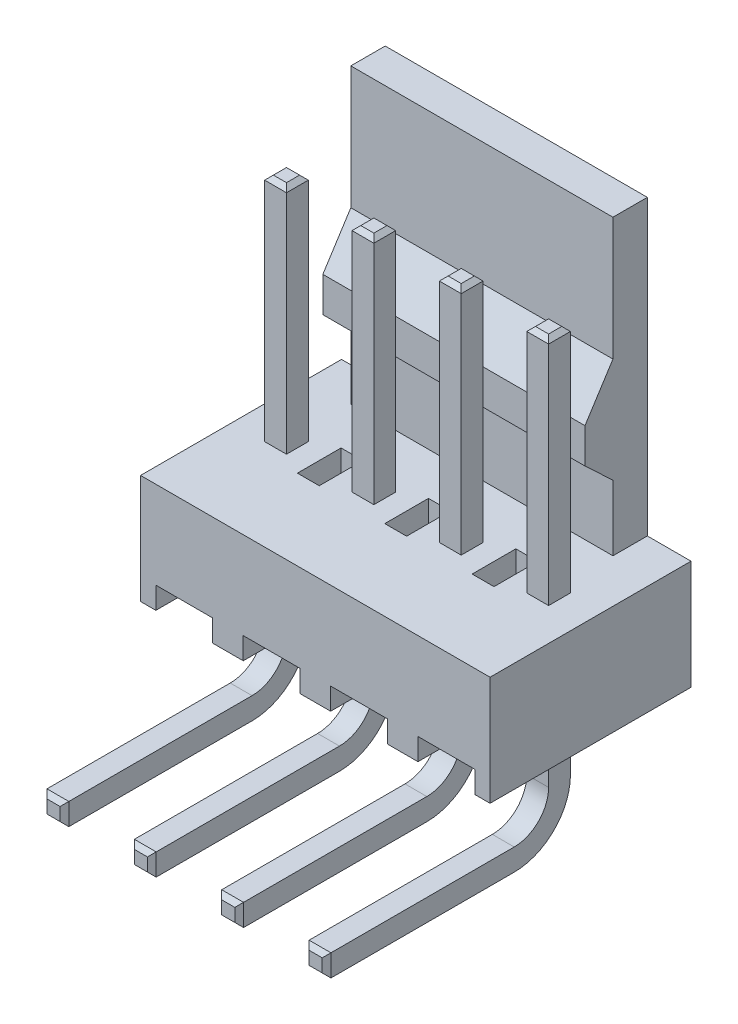
SolidWorks part; units mm, degrees
ref_plane "Front" through (0, 0, 0) normal (0, 0, 1) x (1, 0, 0)
ref_plane "Top" through (0, 0, 0) normal (0, 1, 0) x (1, 0, 0)
ref_plane "Right" through (0, 0, 0) normal (1, 0, 0) x (0, 0, -1)
ref_plane "Plane1" through (0, -1.5875, 0) normal (0, -1, 0) x (1, 0, 0)
sketch "Sketch1" plane through (0, -1.5875, 0) normal (0, -1, 0) x (1, 0, 0)
  line L0 (-5.08, -2.8702) -> (3.81, -2.8702)
  line L1 (3.81, -2.8702) -> (3.81, 2.9718)
  line L2 (3.81, 2.9718) -> (-5.08, 2.9718)
  line L3 (-5.08, 2.9718) -> (-5.08, -2.8702)
extrude "Boss-Extrude1" add sketch "Sketch1" against normal blind 3.175
ref_plane "Plane2" through (3.81, 0, 0) normal (1, 0, 0) x (0, 0, -1)
sketch "Sketch2" plane through (3.81, 0, 0) normal (1, 0, 0) x (0, 0, -1)
  line L0 (0.651, 4.6355) -> (1.8702, 3.4925)
  line L1 (1.8702, 3.4925) -> (1.8702, 1.5875)
  line L2 (1.8702, 1.5875) -> (2.8702, 1.5875)
  line L3 (2.8702, 1.5875) -> (2.8702, 10.1125)
  line L4 (2.8702, 10.1125) -> (1.8702, 10.1125)
  line L5 (1.8702, 10.1125) -> (1.8702, 6.5405)
  line L6 (1.8702, 6.5405) -> (0.651, 4.6355)
extrude "Boss-Extrude2" add sketch "Sketch2" against normal blind 7.62
sketch "Sketch3" plane through (3.81, 0, 0) normal (1, 0, 0) x (0, 0, -1)
  line L0 (-2.9718, 1.5875) -> (2.8702, 1.5875)
  line L1 (2.8702, 1.5875) -> (2.8702, -1.5875)
  line L2 (2.8702, -1.5875) -> (-2.9718, -1.5875)
  line L3 (-2.9718, -1.5875) -> (-2.9718, 1.5875)
extrude "Boss-Extrude3" add sketch "Sketch3" along normal blind 1.27
sketch "Sketch4" plane through (0, 0, -2.8702) normal (0, 0, -1) x (-1, 0, 0)
  line L0 (0.4445, -1.5875) -> (2.0955, -1.5875)
  line L1 (2.0955, -1.5875) -> (2.0955, -0.9525)
  line L2 (2.0955, -0.9525) -> (0.4445, -0.9525)
  line L3 (0.4445, -0.9525) -> (0.4445, -1.5875)
extrude "Cut-Extrude1" cut sketch "Sketch4" against normal through all
sketch "Sketch5" plane through (0, -0.9525, 0) normal (0, -1, 0) x (1, 0, 0)
  line L0 (-0.9525, -0.3175) -> (-1.5875, -0.3175)
  line L1 (-1.5875, -0.3175) -> (-1.5875, 0.3175)
  line L2 (-1.5875, 0.3175) -> (-0.9525, 0.3175)
  line L3 (-0.9525, 0.3175) -> (-0.9525, -0.3175)
extrude "Boss-Extrude4" add sketch "Sketch5" along normal blind 3.6725
sketch "Sketch6" plane through (0, 0, 0.3175) normal (0, 0, 1) x (1, 0, 0)
  line L0 (-0.9525, -3.99) -> (-0.9525, -4.625)
  line L1 (-0.9525, -4.625) -> (-1.5875, -4.625)
  line L2 (-1.5875, -4.625) -> (-1.5875, -3.99)
  line L3 (-1.5875, -3.99) -> (-0.9525, -3.99)
extrude "Boss-Extrude5" add sketch "Sketch6" along normal blind 6.4543
sketch "Sketch7" plane through (0, 0, -2.8702) normal (0, 0, -1) x (-1, 0, 0)
  line L0 (-2.0955, -1.5875) -> (-0.4445, -1.5875)
  line L1 (-0.4445, -1.5875) -> (-0.4445, -0.9525)
  line L2 (-0.4445, -0.9525) -> (-2.0955, -0.9525)
  line L3 (-2.0955, -0.9525) -> (-2.0955, -1.5875)
extrude "Cut-Extrude2" cut sketch "Sketch7" against normal through all
sketch "Sketch8" plane through (0, -0.9525, 0) normal (0, -1, 0) x (1, 0, 0)
  line L0 (1.5875, -0.3175) -> (0.9525, -0.3175)
  line L1 (0.9525, -0.3175) -> (0.9525, 0.3175)
  line L2 (0.9525, 0.3175) -> (1.5875, 0.3175)
  line L3 (1.5875, 0.3175) -> (1.5875, -0.3175)
extrude "Boss-Extrude6" add sketch "Sketch8" along normal blind 3.6725
sketch "Sketch9" plane through (0, 0, 0.3175) normal (0, 0, 1) x (1, 0, 0)
  line L0 (1.5875, -4.625) -> (0.9525, -4.625)
  line L1 (0.9525, -4.625) -> (0.9525, -3.99)
  line L2 (0.9525, -3.99) -> (1.5875, -3.99)
  line L3 (1.5875, -3.99) -> (1.5875, -4.625)
extrude "Boss-Extrude7" add sketch "Sketch9" along normal blind 6.4543
sketch "Sketch10" plane through (0, 0, -2.8702) normal (0, 0, -1) x (-1, 0, 0)
  line L0 (2.9845, -1.5875) -> (4.6355, -1.5875)
  line L1 (4.6355, -1.5875) -> (4.6355, -0.9525)
  line L2 (4.6355, -0.9525) -> (2.9845, -0.9525)
  line L3 (2.9845, -0.9525) -> (2.9845, -1.5875)
extrude "Cut-Extrude3" cut sketch "Sketch10" against normal through all
sketch "Sketch11" plane through (0, -0.9525, 0) normal (0, -1, 0) x (1, 0, 0)
  line L0 (-3.4925, -0.3175) -> (-4.1275, -0.3175)
  line L1 (-4.1275, -0.3175) -> (-4.1275, 0.3175)
  line L2 (-4.1275, 0.3175) -> (-3.4925, 0.3175)
  line L3 (-3.4925, 0.3175) -> (-3.4925, -0.3175)
extrude "Boss-Extrude8" add sketch "Sketch11" along normal blind 3.6725
sketch "Sketch12" plane through (0, 0, 0.3175) normal (0, 0, 1) x (1, 0, 0)
  line L0 (-3.4925, -4.625) -> (-4.1275, -4.625)
  line L1 (-4.1275, -4.625) -> (-4.1275, -3.99)
  line L2 (-4.1275, -3.99) -> (-3.4925, -3.99)
  line L3 (-3.4925, -3.99) -> (-3.4925, -4.625)
extrude "Boss-Extrude9" add sketch "Sketch12" along normal blind 6.4543
sketch "Sketch13" plane through (0, 0, -2.8702) normal (0, 0, -1) x (-1, 0, 0)
  line L0 (-4.6355, -1.5875) -> (-2.9845, -1.5875)
  line L1 (-2.9845, -1.5875) -> (-2.9845, -0.9525)
  line L2 (-2.9845, -0.9525) -> (-4.6355, -0.9525)
  line L3 (-4.6355, -0.9525) -> (-4.6355, -1.5875)
extrude "Cut-Extrude4" cut sketch "Sketch13" against normal through all
sketch "Sketch14" plane through (0, -0.9525, 0) normal (0, -1, 0) x (1, 0, 0)
  line L0 (4.1275, -0.3175) -> (3.4925, -0.3175)
  line L1 (3.4925, -0.3175) -> (3.4925, 0.3175)
  line L2 (3.4925, 0.3175) -> (4.1275, 0.3175)
  line L3 (4.1275, 0.3175) -> (4.1275, -0.3175)
extrude "Boss-Extrude10" add sketch "Sketch14" along normal blind 3.6725
sketch "Sketch15" plane through (0, 0, 0.3175) normal (0, 0, 1) x (1, 0, 0)
  line L0 (4.1275, -4.625) -> (3.4925, -4.625)
  line L1 (3.4925, -4.625) -> (3.4925, -3.99)
  line L2 (3.4925, -3.99) -> (4.1275, -3.99)
  line L3 (4.1275, -3.99) -> (4.1275, -4.625)
extrude "Boss-Extrude11" add sketch "Sketch15" along normal blind 6.4543
sketch "Sketch16" plane through (0, 1.5875, 0) normal (0, 1, 0) x (-1, 0, 0)
  line L0 (-4.1275, 0.3175) -> (-3.4925, 0.3175)
  line L1 (-3.4925, 0.3175) -> (-3.4925, -0.3175)
  line L2 (-3.4925, -0.3175) -> (-4.1275, -0.3175)
  line L3 (-4.1275, -0.3175) -> (-4.1275, 0.3175)
extrude "Boss-Extrude12" add sketch "Sketch16" along normal blind 6.71
sketch "Sketch17" plane through (0, 1.5875, 0) normal (0, 1, 0) x (-1, 0, 0)
  line L0 (-0.9525, -0.3175) -> (-1.5875, -0.3175)
  line L1 (-1.5875, -0.3175) -> (-1.5875, 0.3175)
  line L2 (-1.5875, 0.3175) -> (-0.9525, 0.3175)
  line L3 (-0.9525, 0.3175) -> (-0.9525, -0.3175)
extrude "Boss-Extrude13" add sketch "Sketch17" along normal blind 6.71
sketch "Sketch18" plane through (0, 1.5875, 0) normal (0, 1, 0) x (-1, 0, 0)
  line L0 (0.9525, 0.3175) -> (1.5875, 0.3175)
  line L1 (1.5875, 0.3175) -> (1.5875, -0.3175)
  line L2 (1.5875, -0.3175) -> (0.9525, -0.3175)
  line L3 (0.9525, -0.3175) -> (0.9525, 0.3175)
extrude "Boss-Extrude14" add sketch "Sketch18" along normal blind 6.71
sketch "Sketch19" plane through (0, 1.5875, 0) normal (0, 1, 0) x (-1, 0, 0)
  line L0 (3.4925, -0.3175) -> (3.4925, 0.3175)
  line L1 (3.4925, 0.3175) -> (4.1275, 0.3175)
  line L2 (4.1275, 0.3175) -> (4.1275, -0.3175)
  line L3 (4.1275, -0.3175) -> (3.4925, -0.3175)
extrude "Boss-Extrude15" add sketch "Sketch19" along normal blind 6.71
sketch "Sketch20" plane through (0, 1.5875, 0) normal (0, 1, 0) x (-1, 0, 0)
  line L0 (-2.8575, 0.635) -> (-2.8575, -0.635)
  line L1 (-2.8575, -0.635) -> (-2.2225, -0.635)
  line L2 (-2.2225, -0.635) -> (-2.2225, 0.635)
  line L3 (-2.2225, 0.635) -> (-2.8575, 0.635)
extrude "Cut-Extrude5" cut sketch "Sketch20" against normal blind 1.27
sketch "Sketch21" plane through (0, 1.5875, 0) normal (0, 1, 0) x (-1, 0, 0)
  line L0 (-0.3175, 0.635) -> (-0.3175, -0.635)
  line L1 (-0.3175, -0.635) -> (0.3175, -0.635)
  line L2 (0.3175, -0.635) -> (0.3175, 0.635)
  line L3 (0.3175, 0.635) -> (-0.3175, 0.635)
extrude "Cut-Extrude6" cut sketch "Sketch21" against normal blind 1.27
sketch "Sketch22" plane through (0, 1.5875, 0) normal (0, 1, 0) x (-1, 0, 0)
  line L0 (2.2225, 0.635) -> (2.2225, -0.635)
  line L1 (2.2225, -0.635) -> (2.8575, -0.635)
  line L2 (2.8575, -0.635) -> (2.8575, 0.635)
  line L3 (2.8575, 0.635) -> (2.2225, 0.635)
extrude "Cut-Extrude7" cut sketch "Sketch22" against normal blind 1.27
chamfer "Chamfer1" distance 0.127 angle 45 32 edges at (-3.81, -3.99, 6.7718) (-4.1275, -4.3075, 6.7718) (-3.4925, -4.3075, 6.7718) (-3.81, -4.625, 6.7718) (-1.5875, 8.2975, 0) (-1.27, 8.2975, -0.3175) (-1.27, 8.2975, 0.3175) (-0.9525, 8.2975, 0) (-3.81, 8.2975, 0.3175) (-4.1275, 8.2975, 0) (-3.4925, 8.2975, 0) (-3.81, 8.2975, -0.3175) (-1.5875, -4.3075, 6.7718) (-1.27, -3.99, 6.7718) (-1.27, -4.625, 6.7718) (-0.9525, -4.3075, 6.7718) (3.81, -3.99, 6.7718) (3.4925, -4.3075, 6.7718) (4.1275, -4.3075, 6.7718) (3.81, -4.625, 6.7718) (3.4925, 8.2975, 0) (3.81, 8.2975, -0.3175) (3.81, 8.2975, 0.3175) (4.1275, 8.2975, 0) (1.27, -3.99, 6.7718) (0.9525, -4.3075, 6.7718) (1.5875, -4.3075, 6.7718) (1.27, -4.625, 6.7718) (1.5875, 8.2975, 0) (1.27, 8.2975, 0.3175) (1.27, 8.2975, -0.3175) (0.9525, 8.2975, 0)
chamfer "Chamfer2" distance 0.7539 angle 32.619 1 edges at (0, 4.6355, -0.651)
fillet "Fillet1" radius 1 4 edges at (1.27, -3.99, 0.3175) (-3.81, -3.99, 0.3175) (-1.27, -3.99, 0.3175) (3.81, -3.99, 0.3175)
fillet "Fillet2" radius 1.635 4 edges at (1.27, -4.625, -0.3175) (-3.81, -4.625, -0.3175) (3.81, -4.625, -0.3175) (-1.27, -4.625, -0.3175)
sketch "Sketch23" plane through (0, 8.2975, 0) normal (0, 1, 0) x (1, 0, 0)
  line L0 (-4.0005, -0.1905) -> (-3.6195, 0.1905) construction
  line L1 (-4.0005, 0) -> (-3.6195, 0) construction
  line L2 (-4.0005, 0.1905) -> (-4.0005, -0.1905) construction
  line L3 (-3.6195, -0.1905) -> (-3.6195, 0.1905) construction
  line L4 (3.6195, 0) -> (4.0005, 0) construction
  line L5 (3.6195, 0.1905) -> (3.6195, -0.1905) construction
  line L6 (4.0005, -0.1905) -> (4.0005, 0.1905) construction
  circle A0 centre (-3.81, 0) radius 0.127 construction
  circle A1 centre (3.81, 0) radius 0.127 construction
  dimension "D1" = 0.254
  dimension "D2" = 0.254
sketch "Sketch24" plane through (0, 0, 6.7718) normal (0, 0, 1) x (1, 0, 0)
  line L0 (-4.0005, -4.3075) -> (4.0005, -4.3075) construction
  line L1 (-4.0005, -4.117) -> (-4.0005, -4.498) construction
  line L2 (4.0005, -4.498) -> (4.0005, -4.117) construction
  line L3 (-3.81, -4.498) -> (-3.81, -4.117) construction
  line L4 (-4.0005, -4.498) -> (-3.6195, -4.498) construction
  line L5 (-3.6195, -4.117) -> (-4.0005, -4.117) construction
  line L6 (3.81, -4.498) -> (3.81, -4.117) construction
  line L7 (3.6195, -4.498) -> (4.0005, -4.498) construction
  line L8 (4.0005, -4.117) -> (3.6195, -4.117) construction
  line L9 (3.81, -50) -> (3.81, 50) construction
  circle A0 centre (-3.81, -4.3075) radius 0.127 construction
  circle A1 centre (3.81, -4.3075) radius 0.127 construction
  point P22 (3.4357, -4.3075)
  point P23 (0.48, -5.0984)
  point P24 (-2.5346, -4.3075)
  point P25 (-3.81, -4.3075)
  point P26 (3.81, -4.3075)
  dimension "D1" = 0.254
  dimension "D2" = 0.254
